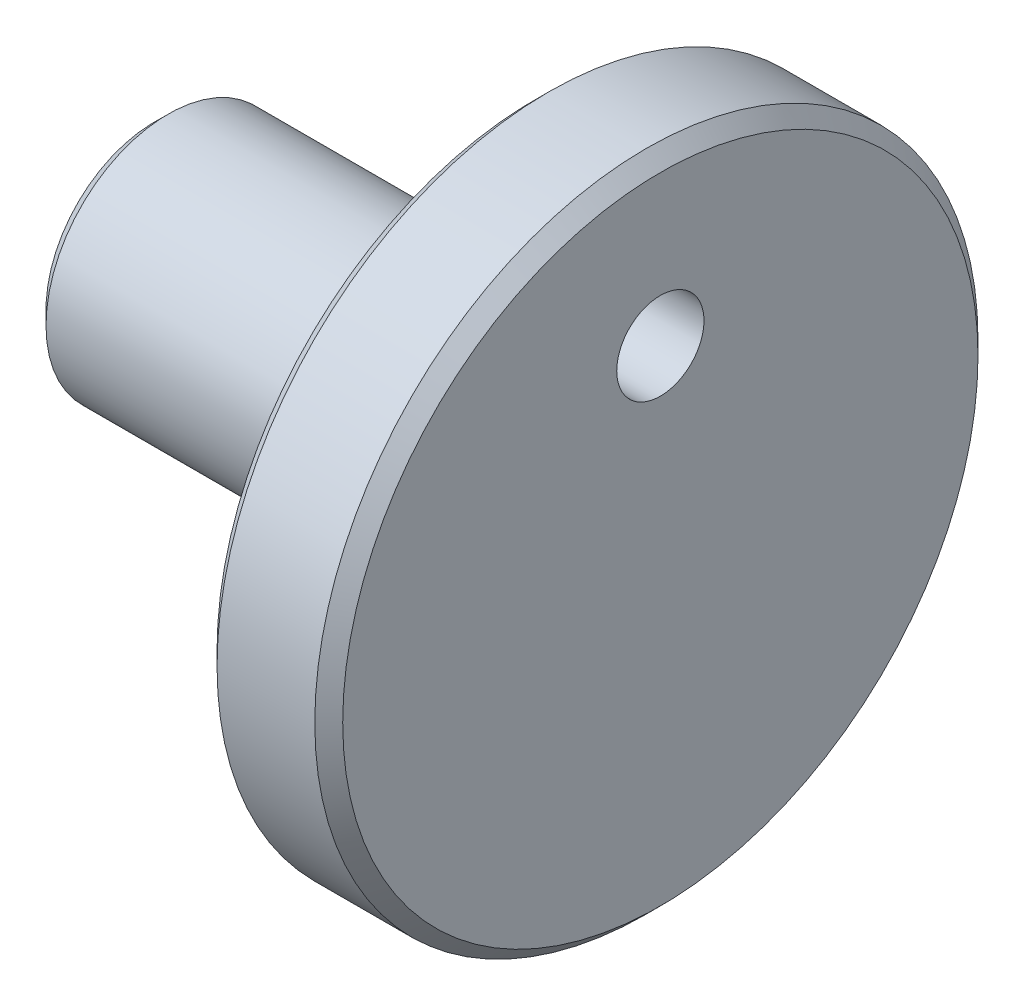
SolidWorks part; units mm, degrees
material "3.0205 (EN-AW 1200)"
ref_plane "Спереди" through (0, 0, 0) normal (0, 0, 1) x (1, 0, 0)
ref_plane "Сверху" through (0, 0, 0) normal (0, 1, 0) x (1, 0, 0)
ref_plane "Справа" through (0, 0, 0) normal (1, 0, 0) x (0, 0, -1)
sketch "Эскиз2" plane through (0, 0, 0) normal (0, 0, 1) x (1, 0, 0)
  line L0 (0, 0) -> (0, 9.5)
  line L1 (0, 9.5) -> (-3.6, 9.5)
  line L2 (-3.6, 9.5) -> (-3.6, 3.5)
  line L3 (-3.6, 3.5) -> (-14.5, 3.5)
  line L4 (-14.5, 3.5) -> (-14.5, 0)
  line L5 (-14.5, 0) -> (0, 0) construction
  line L6 (0, 0) -> (-14.5, 0)
  dimension "D1" = 10.9
  dimension "D2" = 14.5
  dimension "D3" = 3.5
  dimension "D4" = 9.5
revolve "Повернуть1" add sketch "Эскиз2" angle 360 about L5
sketch "Эскиз3" plane through (-3.6, 0, 0) normal (-1, 0, 0) x (0, 0, 1)
  circle A0 centre (0, 4.8) radius 1.25
  dimension "D1" = 2.5
  dimension "D2" = 4.8
extrude "Вырез-Вытянуть1" cut sketch "Эскиз3" against normal through all contours A0
chamfer "Фаска1" distance 0.4 angle 45 3 edges at (-14.5, 0, 3.5) (0, 0, 9.5) (-3.6, 0, 9.5)
